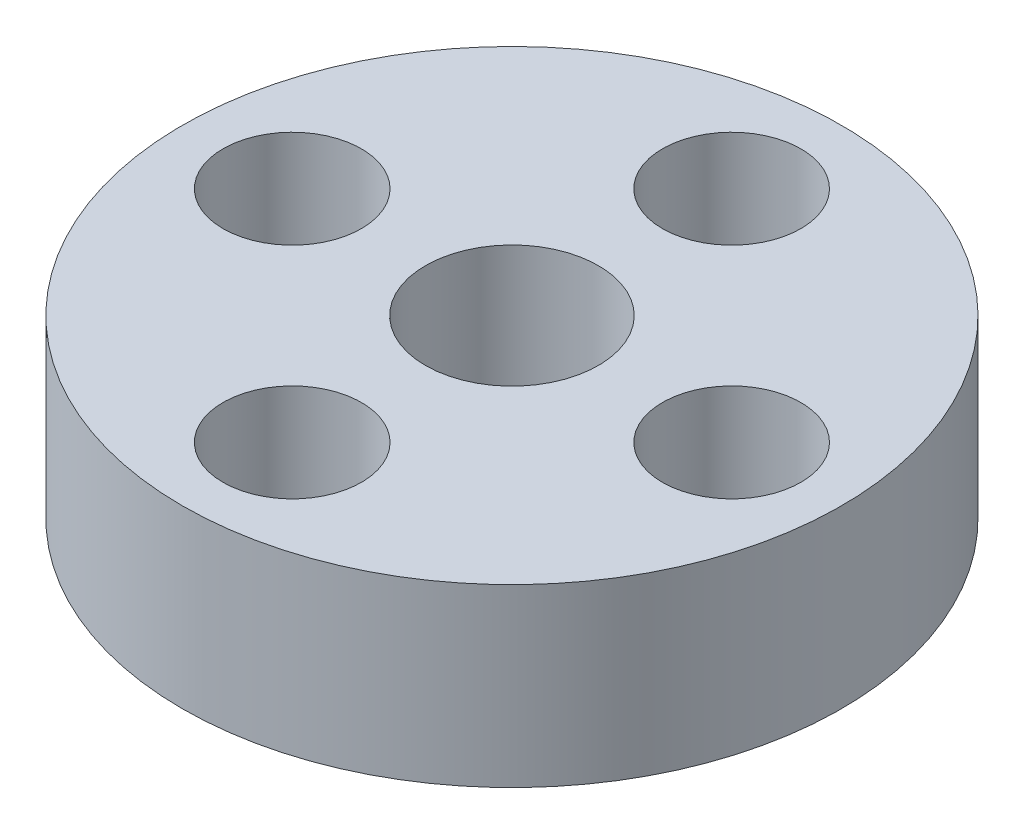
SolidWorks part; units mm, degrees
ref_plane "Plan de face" through (0, 0, 0) normal (0, 0, 1) x (1, 0, 0)
ref_plane "Plan de dessus" through (0, 0, 0) normal (0, 1, 0) x (1, 0, 0)
ref_plane "Plan de droite" through (0, 0, 0) normal (1, 0, 0) x (0, 0, -1)
sketch "Esquisse1" plane through (0, 0, 0) normal (0, 1, 0) x (1, 0, 0)
  circle A0 centre (0, 0) radius 9.525
  dimension "D1" = 19.05
extrude "Boss.-Extru.1" add sketch "Esquisse1" along normal blind 5.08
sketch "Esquisse2" plane through (0, 5.08, 0) normal (0, 1, 0) x (1, 0, 0)
  line L0 (0.9162, 0) -> (-8.6088, 0) construction
  circle A0 centre (0, 6.35) radius 2
  circle A1 centre (-6.35, 0) radius 2
  circle A2 centre (6.35, 0) radius 2
  circle A3 centre (0, -6.35) radius 2
  circle A4 centre (0, 0) radius 2.5
  point P2 (0, 0)
  point P15 (0, 0)
  dimension "D1" = 4
  dimension "D4" = 5
  dimension "D2" = 6.35
  dimension "D3" = 4
extrude "Enlèv. mat.-Extru.1" cut sketch "Esquisse2" against normal through all
